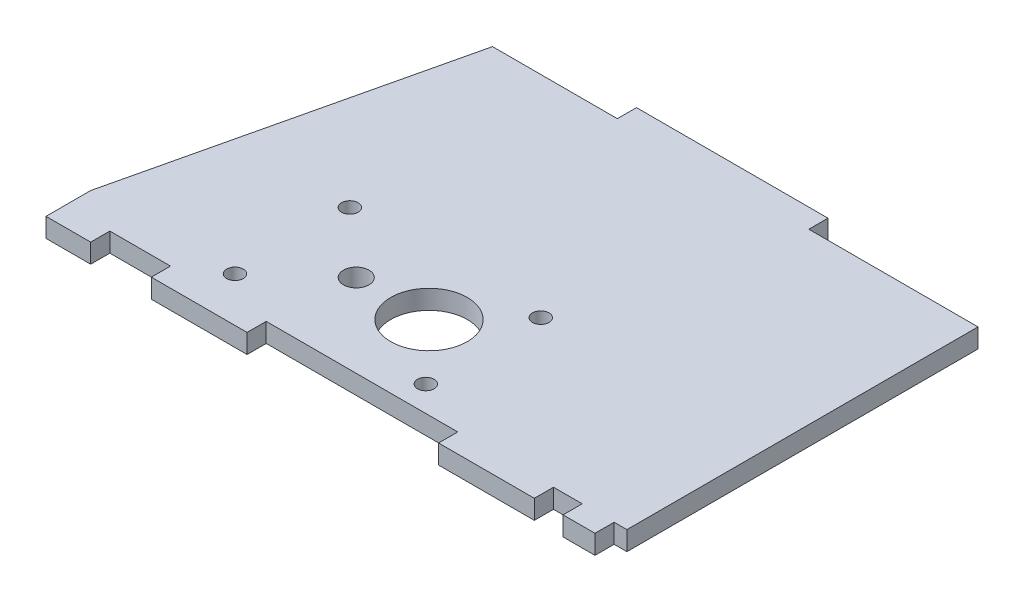
SolidWorks part; units mm, degrees
ref_plane "Front Plane" through (0, 0, 0) normal (0, 0, 1) x (1, 0, 0)
ref_plane "Top Plane" through (0, 0, 0) normal (0, 1, 0) x (1, 0, 0)
ref_plane "Right Plane" through (0, 0, 0) normal (1, 0, 0) x (0, 0, -1)
sketch "Sketch1" plane through (0, 0, 0) normal (0, 1, 0) x (1, 0, 0)
  line L0 (-95.4834, 27.7677) -> (-80.4834, 27.7677)
  line L1 (-80.4834, 27.7677) -> (-80.4834, 30.7677)
  line L2 (-80.4834, 30.7677) -> (-50.4834, 30.7677)
  line L3 (-95.4834, -30.2323) -> (-80.4834, -30.2323)
  line L4 (-80.4834, -30.2323) -> (-80.4834, -27.2323)
  line L5 (-80.4834, -27.2323) -> (-50.4834, -27.2323)
  line L6 (-50.4834, -30.2323) -> (-50.4834, -27.2323)
  line L7 (-35.4834, -30.2323) -> (-50.4834, -30.2323)
  line L8 (-50.4834, 27.7677) -> (-50.4834, 30.7677)
  line L9 (-35.4834, 27.7677) -> (-50.4834, 27.7677)
  line L10 (-35.4834, -30.2323) -> (-35.4834, -27.2323)
  line L11 (-35.4834, -27.2323) -> (-30.9834, -27.2323)
  line L12 (-30.9834, -27.2323) -> (-30.9834, -30.2323)
  line L13 (-30.9834, -30.2323) -> (-25.9834, -30.2323)
  line L14 (-104.9834, -30.2323) -> (-104.9834, -27.2323)
  line L15 (-111.9834, -27.2323) -> (-111.9834, -30.2323)
  line L16 (-111.9834, -30.2323) -> (-104.9834, -30.2323)
  line L17 (-104.9834, -27.2323) -> (-95.4834, -27.2323)
  line L18 (-95.4834, -27.2323) -> (-95.4834, -30.2323)
  line L19 (-111.9834, -27.2323) -> (-111.9834, -23.2323)
  line L20 (-35.4834, 27.7677) -> (-25.9834, 27.7677)
  line L27 (-95.4834, 27.7677) -> (-100.0334, 27.7677)
  line L28 (-100.0334, 27.7677) -> (-111.9834, -23.2323)
  line L30 (-25.9834, -27.2323) -> (-23.9834, -27.2323)
  line L31 (-23.9834, -27.2323) -> (-23.9834, 27.7677)
  line L32 (-23.9834, 27.7677) -> (-25.9834, 27.7677)
  line L33 (-25.9834, -30.2323) -> (-25.9834, -27.2323)
  circle A0 centre (-79.3834, -14.2323) radius 2
  circle A1 centre (-67.9834, -14.2323) radius 6
  circle A2 centre (-59.4834, -23.2323) radius 1.3
  circle A3 centre (-59.4834, -5.2323) radius 1.3
  circle A4 centre (-89.3834, -5.2323) radius 1.3
  circle A5 centre (-89.3834, -23.2323) radius 1.3
extrude "Boss-Extrude1" add sketch "Sketch1" along normal blind 3
